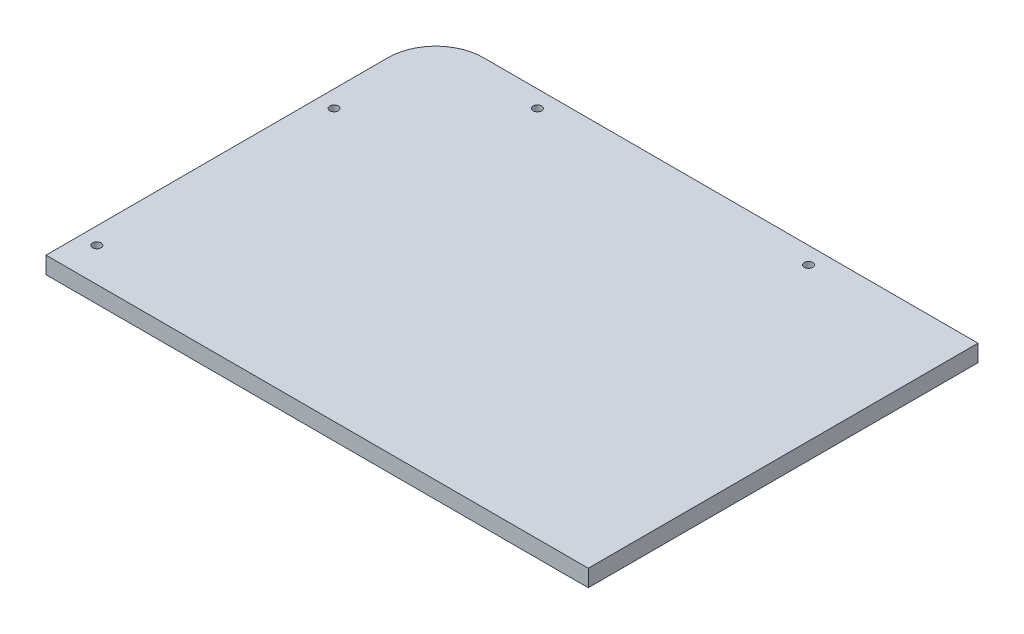
SolidWorks part; units mm, degrees
material "ABS"
ref_plane "Front Plane" through (0, 0, 0) normal (0, 0, 1) x (1, 0, 0)
ref_plane "Top Plane" through (0, 0, 0) normal (0, 1, 0) x (1, 0, 0)
ref_plane "Right Plane" through (0, 0, 0) normal (1, 0, 0) x (0, 0, -1)
sketch "Sketch1" plane through (0, 0, 0) normal (0, 1, 0) x (1, 0, 0)
  line L1 (0, 0) -> (203.2, 0)
  line L2 (0, 0) -> (0, 128.27)
  line L3 (17.78, 146.05) -> (203.2, 146.05)
  line L4 (203.2, 0) -> (203.2, 146.05)
  circle A0 centre (6.35, 12.7) radius 1.5875
  arc A1 (17.78, 146.05) -> (0, 128.27) centre (17.78, 128.27) ccw
  circle A2 centre (6.35, 101.6) radius 1.5875
  circle A3 centre (44.45, 139.7) radius 1.5875
  circle A4 centre (146.05, 139.7) radius 1.5875
  point P9 (0, 146.05)
  dimension "D3" = 17.78
  dimension "D4" = 3.175
  dimension "D1" = 146.05
  dimension "D2" = 203.2
  dimension "D5" = 6.35
  dimension "D6" = 12.7
  dimension "D7" = 88.9
  dimension "D8" = 6.35
  dimension "D9" = 57.15
  dimension "D10" = 101.6
extrude "Boss-Extrude1" add sketch "Sketch1" along normal blind 6.35
